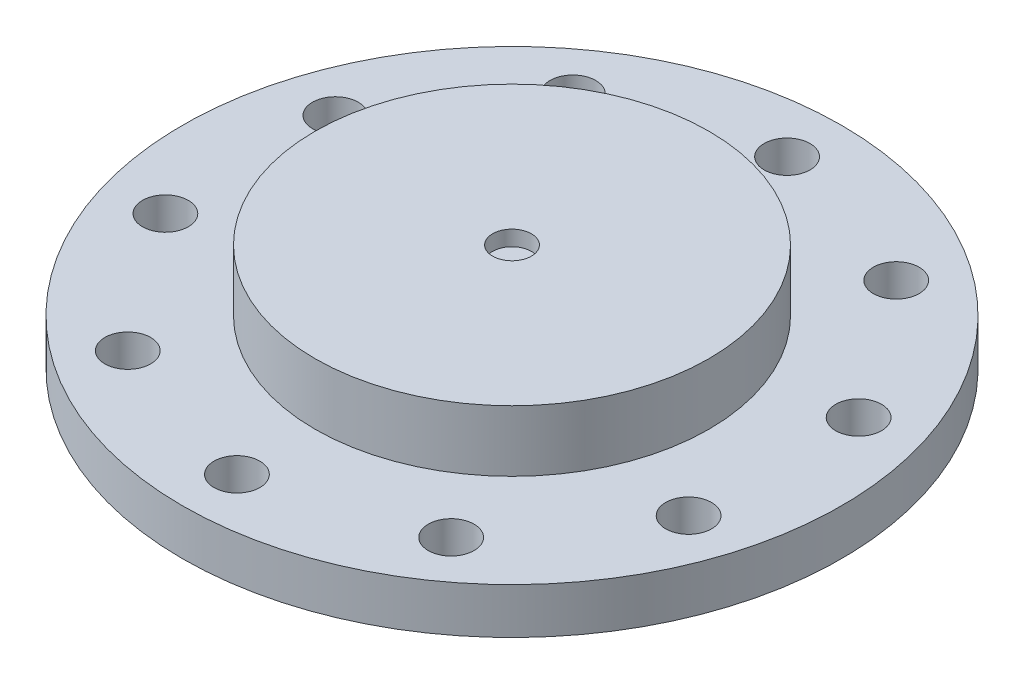
SolidWorks part; units mm, degrees
ref_plane "Front Plane" through (0, 0, 0) normal (0, 0, 1) x (1, 0, 0)
ref_plane "Top Plane" through (0, 0, 0) normal (0, 1, 0) x (1, 0, 0)
ref_plane "Right Plane" through (0, 0, 0) normal (1, 0, 0) x (0, 0, -1)
sketch "Sketch2" plane through (0, 0, 0) normal (0, 1, 0) x (1, 0, 0)
  circle A0 centre (0, 0) radius 107.8268
  circle A1 centre (0, 90) radius 7.5
  circle A2 centre (52.9007, 72.8115) radius 7.5
  circle A3 centre (85.5951, 27.8115) radius 7.5
  circle A4 centre (85.5951, -27.8115) radius 7.5
  circle A5 centre (52.9007, -72.8115) radius 7.5
  circle A6 centre (0, -90) radius 7.5
  circle A7 centre (-52.9007, -72.8115) radius 7.5
  circle A8 centre (-85.5951, -27.8115) radius 7.5
  circle A9 centre (-85.5951, 27.8115) radius 7.5
  circle A10 centre (-52.9007, 72.8115) radius 7.5
  point P26 (0, 0)
  dimension "D1" = 215.6537
  dimension "D3" = 15
  dimension "D2" = 90
  dimension "D4" = 10
extrude "Boss-Extrude1" add sketch "Sketch2" along normal blind 15
sketch "Sketch3" plane through (0, 0, 0) normal (0, -1, 0) x (1, 0, 0)
  circle A0 centre (0, 0) radius 71.687
  circle A1 centre (0, 0) radius 64.4478
  dimension "D1" = 143.374
  dimension "D2" = 128.8957
extrude "Cut-Extrude1" cut sketch "Sketch3" against normal blind 3
sketch "Sketch4" plane through (0, 15, 0) normal (0, 1, 0) x (1, 0, 0)
  line L0 (0, 47.8268) -> (22.9469, 47.8268) construction
  line L1 (0, 64.4478) -> (21.588, 64.4478) construction
  line L3 (-1.5, 57.8268) -> (1.5, 57.8268)
  line L4 (-1.5, 57.8268) -> (-1.5, 52.8268)
  line L5 (-1.5, 52.8268) -> (1.5, 52.8268)
  line L6 (1.5, 57.8268) -> (1.5, 52.8268)
  circle A0 centre (0, 0) radius 64.4478 construction
  circle A1 centre (0, 0) radius 71.687 construction
  circle A2 centre (0, 0) radius 47.8268 construction
  point P13 (0, 52.8268)
  dimension "D1" = 143.374
  dimension "D2" = 128.8957
  dimension "D3" = 95.6537
  dimension "D4" = 5
  dimension "D5" = 5
  dimension "D6" = 3
extrude "Cut-Extrude2" cut sketch "Sketch4" against normal through all
pattern_circular "CirPattern1" count 35 over 360 about axis through (0, 0, 0) along (0, 1, 0) of "Cut-Extrude2"
sketch "Sketch6" plane through (0, 15, 0) normal (0, 1, 0) x (1, 0, 0)
  circle A0 centre (0, 0) radius 64.4478
  circle A1 centre (0, 0) radius 6.35
  dimension "D1" = 128.8957
  dimension "D3" = 12.7
extrude "Boss-Extrude3" add sketch "Sketch6" along normal blind 10 separate body
sketch "Sketch8" plane through (0, 25, 0) normal (0, 1, 0) x (1, 0, 0)
  line L0 (0, 47.8268) -> (22.9469, 47.8268) construction
  line L1 (0, 64.4478) -> (21.588, 64.4478) construction
  line L3 (-1.5, 57.8268) -> (1.5, 57.8268)
  line L4 (-1.5, 57.8268) -> (-1.5, 52.8268)
  line L5 (-1.5, 52.8268) -> (1.5, 52.8268)
  line L6 (1.5, 57.8268) -> (1.5, 52.8268)
  circle A0 centre (0, 0) radius 64.4478 construction
  circle A1 centre (0, 0) radius 71.687 construction
  circle A2 centre (0, 0) radius 47.8268 construction
  point P13 (0, 52.8268)
  dimension "D1" = 143.374
  dimension "D2" = 128.8957
  dimension "D3" = 95.6537
  dimension "D4" = 5
  dimension "D5" = 5
  dimension "D6" = 3
extrude "Cut-Extrude4" cut sketch "Sketch8" against normal through all
pattern_circular "CirPattern7" count 35 over 360 about axis through (0, 0, 0) along (0, 1, 0) of "Cut-Extrude4"
sketch "Sketch9" plane through (0, 25, 0) normal (0, 1, 0) x (1, 0, 0)
  circle A0 centre (0, 0) radius 64.4478
  circle A1 centre (0, 0) radius 57.8268
  dimension "D1" = 128.8957
  dimension "D2" = 115.6537
extrude "Boss-Extrude4" add sketch "Sketch9" along normal blind 5
sketch "Sketch10" plane through (0, 30, 0) normal (0, 1, 0) x (1, 0, 0)
  circle A0 centre (0, 0) radius 6.35
  circle A1 centre (0, 0) radius 64.4478
  dimension "D2" = 128.8957
  dimension "D1" = 12.7
extrude "Boss-Extrude5" add sketch "Sketch10" along normal blind 5
sketch "Sketch11" plane through (0, 15, 0) normal (0, 1, 0) x (1, 0, 0)
  circle A0 centre (0, 0) radius 36.6524
  circle A2 centre (0, 0) radius 47.8268
  dimension "D1" = 73.3048
  dimension "D2" = 95.6537
extrude "Boss-Extrude7" add sketch "Sketch11" along normal blind 10
sketch "Sketch12" plane through (0, 15, 0) normal (0, 1, 0) x (1, 0, 0)
  circle A0 centre (0, 0) radius 6.35
  dimension "D1" = 12.7
extrude "Cut-Extrude5" cut sketch "Sketch12" against normal through all
sketch "Sketch13" plane through (0, 25, 0) normal (0, 1, 0) x (1, 0, 0)
  circle A0 centre (0, 0) radius 35 construction
  circle A1 centre (0, 35) radius 0.8262
  circle A2 centre (30.3109, -17.5) radius 0.8262
  circle A3 centre (-30.3109, -17.5) radius 0.8262
  point P12 (0, 0)
  dimension "D1" = 70
  dimension "D2" = 1.6524
  dimension "D3" = 3
extrude "Cut-Extrude6" cut sketch "Sketch13" against normal through all
equation "\"FuelDia\"= 1.6524"
equation "\"OxDia\"=1.82924"
equation "\"DistOrifice\"= 10"
equation "\"CantAngle\"= 25deg"
equation "\"RadialDistOrifice\"= 60"
equation "\"Chan_amt\"= 35"
equation "\"Chan_wid\"= 3"
equation "\"Chan_heig\"= 5"
equation "\"bolt_diam\"= 15"
equation "\"oring_inner\"= 128.8956920"
equation "\"oring_outer\"=143.374"
equation "\"oring_thickness\"=3"
equation "\"D3@Sketch2\"=\"bolt_diam\""
equation "\"D1@Sketch3\"=\"oring_outer\""
equation "\"D2@Sketch3\"=\"oring_inner\""
equation "\"D1@Cut-Extrude1\"=\"oring_thickness\""
equation "\"D1@Sketch4\"=\"oring_outer\""
equation "\"D2@Sketch4\"=\"oring_inner\""
equation "\"D3@Sketch4\"=95.6536920"
equation "\"D5@Sketch4\"=\"Chan_heig\""
equation "\"D6@Sketch4\"=\"Chan_wid\""
equation "\"D1@CirPattern1\"=\"Chan_amt\""
equation "\"D1@CirPattern7\"=\"Chan_amt\""
equation "\"D1@Sketch9\"=\"oring_inner\""
equation "\"D1@Sketch11\"=\"RadialDistOrifice\"+(\"DistOrifice\") + (2*\"FuelDia\")"
equation "\"TorchIgniter\"=12.7"
equation "\"D1@Sketch10\"=\"TorchIgniter\""
equation "\"D3@Sketch6\"=\"TorchIgniter\""
equation "\"D1@Sketch12\"=\"TorchIgniter\""
equation "\"D2@Sketch13\" = \"FuelDia\""
equation "\"D1@Sketch13\"=\"RadialDistOrifice\" + \"DistOrifice\""
equation "\"t_plate\"=15"
equation "\"D1@Boss-Extrude1\"=\"t_plate\""
